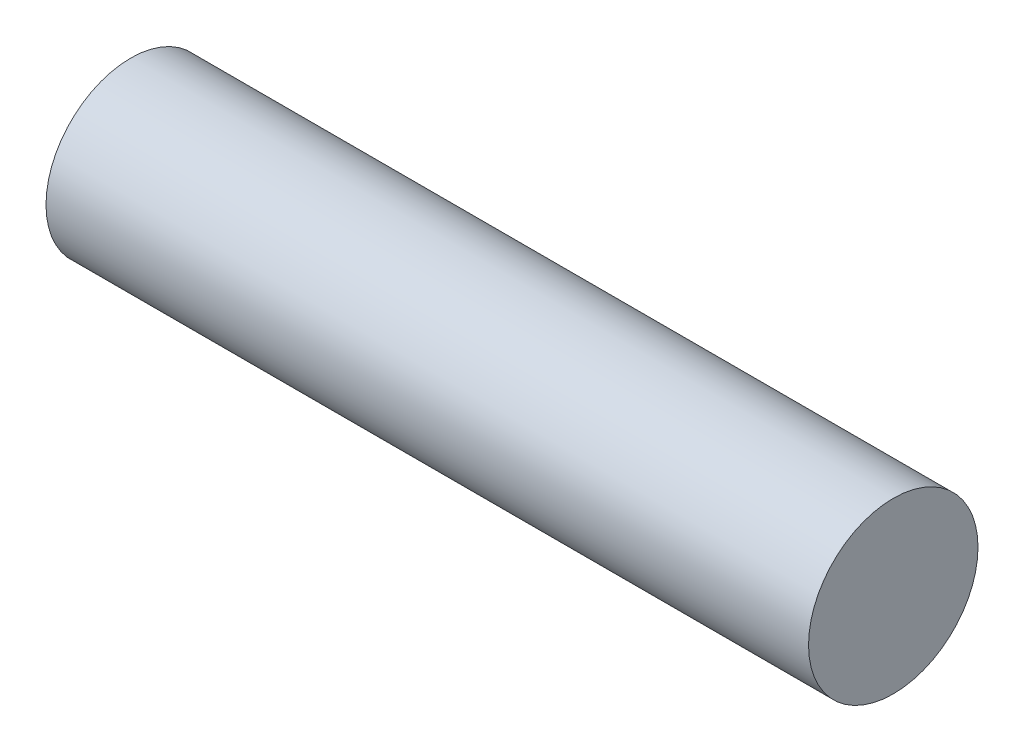
SolidWorks part; units mm, degrees
ref_plane "Front Plane" through (0, 0, 0) normal (0, 0, 1) x (1, 0, 0)
ref_plane "Top Plane" through (0, 0, 0) normal (0, 1, 0) x (1, 0, 0)
ref_plane "Right Plane" through (0, 0, 0) normal (1, 0, 0) x (0, 0, -1)
sketch "Sketch1" plane through (0, 0, 0) normal (1, 0, 0) x (0, 0, -1)
  circle A0 centre (0, 0) radius 1
  dimension "D1" = 2
extrude "Boss-Extrude1" add sketch "Sketch1" along normal blind 9
ref_plane "Plane1" through (9, 0, 0) normal (1, 0, 0) x (0, 0, -1)
